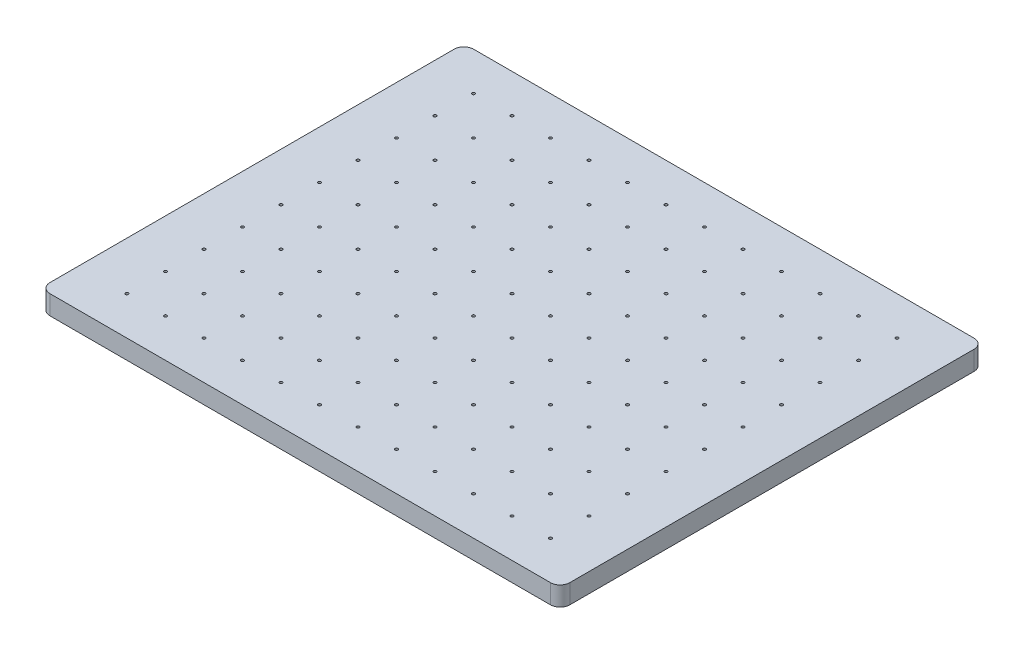
SolidWorks part; units mm, degrees
ref_plane "Front Plane" through (0, 0, 0) normal (0, 0, 1) x (1, 0, 0)
ref_plane "Top Plane" through (0, 0, 0) normal (0, 1, 0) x (1, 0, 0)
ref_plane "Right Plane" through (0, 0, 0) normal (1, 0, 0) x (0, 0, -1)
sketch "Sketch1" plane through (0, 0, 0) normal (0, 1, 0) x (1, 0, 0)
  line L1 (135, -110) -> (-135, -110)
  line L2 (135, -110) -> (135, 110)
  line L3 (135, 110) -> (-135, 110)
  line L4 (-135, -110) -> (-135, 110)
  line L5 (135, -110) -> (-135, 110) construction
  line L6 (135, 110) -> (-135, -110) construction
  point P0 (0, 0)
  dimension "D1" = 270
  dimension "D2" = 220
extrude "Boss-Extrude1" add sketch "Sketch1" along normal blind 10
sketch "Sketch2" plane through (0, 10, 0) normal (0, 1, 0) x (1, 0, 0)
  line L1 (0, 0) -> (0, 110) construction
  line L2 (135, 110) -> (-135, 110) construction
  line L3 (0, 0) -> (-135, 0) construction
  line L4 (-135, 110) -> (-135, -110) construction
  point P0 (-110, 90)
  dimension "D1" = 110
  dimension "D2" = 90
hole_wizard "Ø1.5 (1.5) Diameter Hole1" positions "3DSketch1" profile "Sketch3" hole size "Ø1.5" standard "BSI" end condition through all
sketch3d "3DSketch1"
  point P0 (-110, 10, -90)
sketch "Sketch3" plane through (-110, 10, -90) normal (1, 0, 0) x (0, 0, 1)
  line L0 (0, 0) -> (0, 10)
  line L1 (0, 10) -> (0.75, 10)
  line L2 (0.75, 10) -> (0.75, 0)
  line L5 (0.75, 0) -> (0, 0)
  line L11 (0, -6.35) -> (0, 107.95) construction
  dimension "Thru Hole Dia." = 1.5
  dimension "Thru Hole Depth" = 10
pattern_linear "LPattern1" count 12 spacing 20 along (1, 0, 0) count 10 spacing 20 along (0, 0, 1) of "Ø1.5 (1.5) Diameter Hole1"
fillet "Fillet1" radius 5 4 edges at (135, 5, -110) (135, 5, 110) (-135, 5, 110) (-135, 5, -110)
